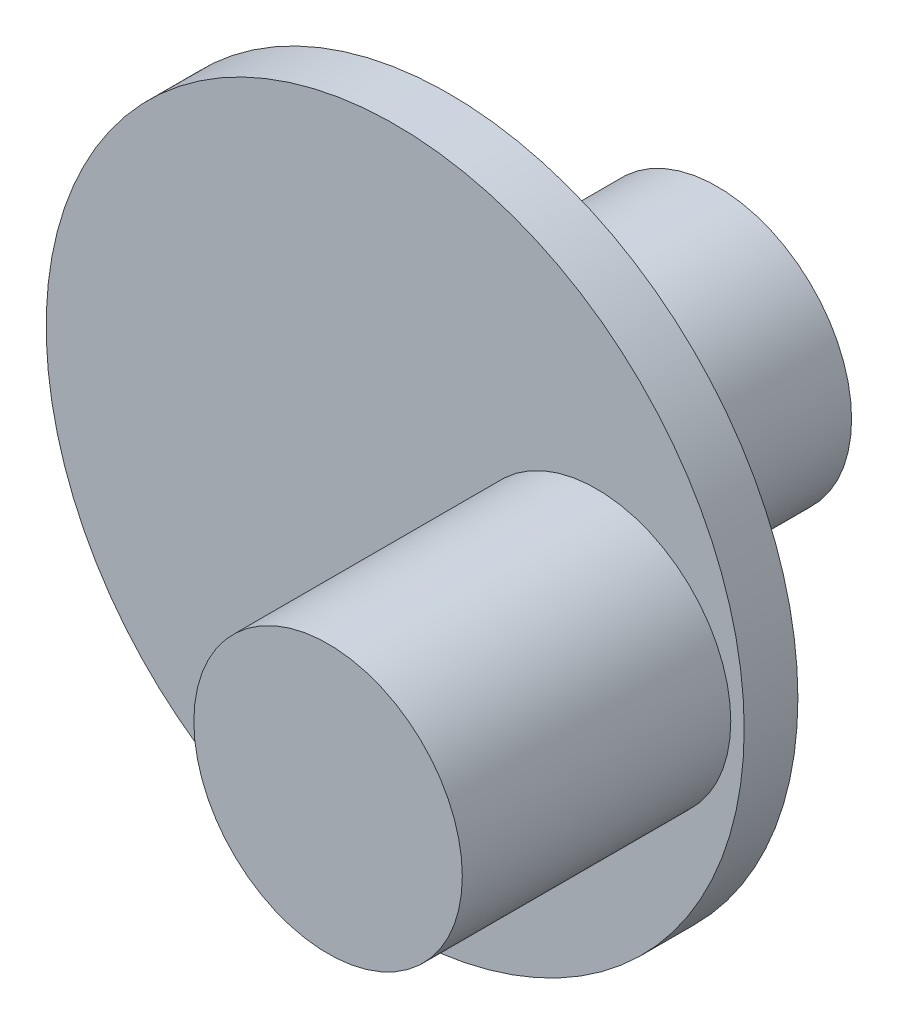
SolidWorks part; units mm, degrees
ref_plane "Plan de face" through (0, 0, 0) normal (0, 0, 1) x (1, 0, 0)
ref_plane "Plan de dessus" through (0, 0, 0) normal (0, 1, 0) x (1, 0, 0)
ref_plane "Plan de droite" through (0, 0, 0) normal (1, 0, 0) x (0, 0, -1)
sketch "Esquisse1" plane through (0, 0, 0) normal (0, 0, 1) x (1, 0, 0)
  circle A0 centre (0, 0) radius 5
  dimension "D1" = 10
extrude "Boss.-Extru.1" add sketch "Esquisse1" along normal blind 10
sketch "Esquisse2" plane through (0, 0, 10) normal (0, 0, 1) x (1, 0, 0)
  circle A0 centre (0, 0) radius 13
  dimension "D1" = 26
extrude "Boss.-Extru.2" add sketch "Esquisse2" along normal blind 2
sketch "Esquisse3" plane through (0, 0, 12) normal (0, 0, 1) x (1, 0, 0)
  circle A0 centre (7.5, 0) radius 5
  dimension "D2" = 10
  dimension "D1" = 7.5
extrude "Boss.-Extru.3" add sketch "Esquisse3" along normal blind 10
